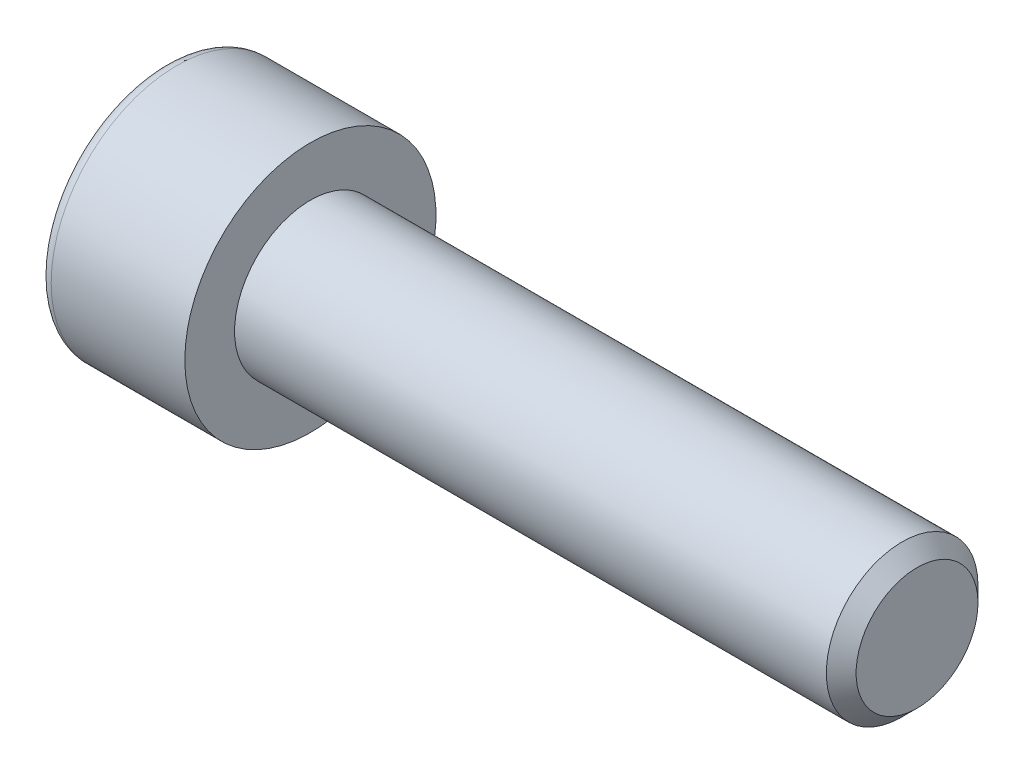
SolidWorks part; units mm, degrees
ref_plane "Front Plane" through (0, 0, 0) normal (0, 0, 1) x (1, 0, 0)
ref_plane "Top Plane" through (0, 0, 0) normal (0, 1, 0) x (1, 0, 0)
ref_plane "Right Plane" through (0, 0, 0) normal (1, 0, 0) x (0, 0, -1)
ref_plane "Plane1" through (0, 0, 0) normal (0, 0, -1) x (-1, 0, 0)
sketch "Sketch1" plane through (0, 0, 0) normal (0, 0, -1) x (-1, 0, 0)
  line L0 (0, 4.14) -> (0, 0)
  line L1 (0, 0) -> (4.82, 0)
  line L2 (4.82, 0) -> (4.82, 4.14)
  line L3 (4.82, 4.14) -> (0, 4.14)
  line L4 (0, 0) -> (4.82, 0) construction
revolve "Revolve1" add sketch "Sketch1" angle 360 about L4
sketch "Sketch2" plane through (0, 0, 0) normal (1, 0, 0) x (0, 0, -1)
  circle A0 centre (0, 0) radius 2.5
extrude "Boss-Extrude1" add sketch "Sketch2" along normal blind 20
sketch "Sketch3" plane through (-4.82, 0, 0) normal (-1, 0, 0) x (0, 0, 1)
  line L0 (-2, -1.1547) -> (0, -2.3094)
  line L1 (0, -2.3094) -> (2, -1.1547)
  line L2 (2, -1.1547) -> (2, 1.1547)
  line L3 (2, 1.1547) -> (0, 2.3094)
  line L4 (0, 2.3094) -> (-2, 1.1547)
  line L5 (-2, 1.1547) -> (-2, -1.1547)
extrude "Cut-Extrude1" cut sketch "Sketch3" against normal blind 2.5
chamfer "Chamfer1" distance 0.4905 angle 45 1 edges at (20, 0, -2.5)
fillet "Fillet1" radius 0.414 1 edges at (-4.82, 0, 4.14)
